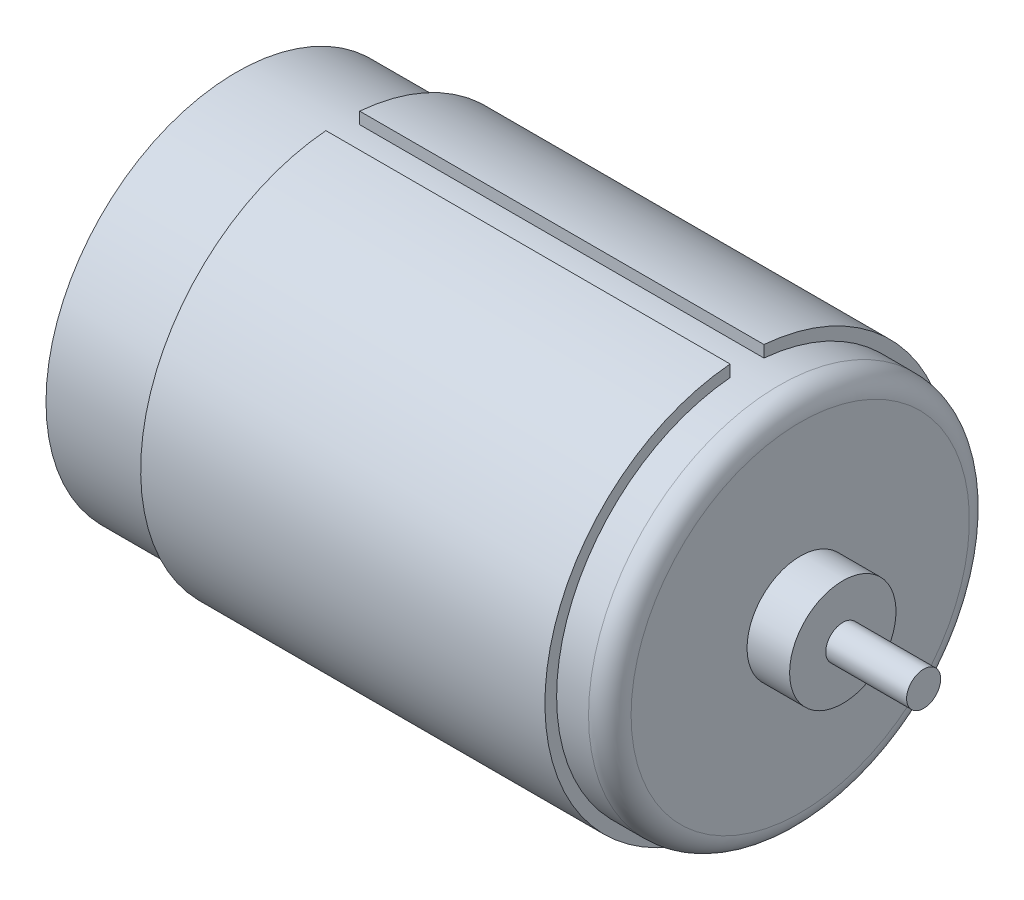
SolidWorks part; units mm, degrees
material "Plain Carbon Steel"
ref_plane "Front Plane" through (0, 0, 0) normal (0, 0, 1) x (1, 0, 0)
ref_plane "Top Plane" through (0, 0, 0) normal (0, 1, 0) x (1, 0, 0)
ref_plane "Right Plane" through (0, 0, 0) normal (1, 0, 0) x (0, 0, -1)
sketch "Sketch3" plane through (0, 0, 0) normal (0, 0, 1) x (1, 0, 0)
  line L0 (0, 0) -> (64.6, 0) construction
  line L1 (0, 0) -> (0, 17.9)
  line L2 (0, 17.9) -> (10, 17.9)
  line L3 (10, 17.9) -> (10, 19)
  line L4 (10, 19) -> (48, 19)
  line L5 (48, 19) -> (48, 17.9)
  line L6 (48, 17.9) -> (51, 17.9)
  line L7 (53, 15.9) -> (53, 5)
  line L8 (53, 5) -> (57, 5)
  line L9 (57, 5) -> (57, 1.6)
  line L10 (57, 1.6) -> (64.6, 1.6)
  line L11 (64.6, 1.6) -> (64.6, 0)
  line L12 (0, 0) -> (4.3018, 0)
  line L13 (49.6755, 14.9017) -> (49.6755, 0)
  line L14 (4.3018, 14.9017) -> (49.6755, 14.9017)
  line L15 (4.3018, 14.9017) -> (4.3018, 0)
  line L16 (49.6755, 0) -> (64.6, 0)
  arc A0 (51, 17.9) -> (53, 15.9) centre (51, 15.9) cw
  point P15 (53, 17.9)
  dimension "D10" = 2
  dimension "D1" = 7.6
  dimension "D2" = 3.2
  dimension "D3" = 57
  dimension "D4" = 35.8
  dimension "D5" = 38
  dimension "D6" = 4
  dimension "D7" = 10
  dimension "D8" = 5
  dimension "D9" = 10
revolve "Revolve1" add sketch "Sketch3" angle 360 about L0
sketch "Sketch4" plane through (10, 0, 0) normal (-1, 0, 0) x (0, 0, 1)
  line L0 (0, 17.9) -> (0, 0) construction
  line L1 (1.5875, 18.9336) -> (1.5875, 17.8295)
  line L2 (-1.5875, 18.9336) -> (-1.5875, 17.8295)
  arc A0 (-1.5875, 17.8295) -> (1.5875, 17.8295) centre (0, 0) cw
  circle A1 centre (0, 0) radius 17.9 construction
  arc A2 (-1.5875, 18.9336) -> (1.5875, 18.9336) centre (0, 0) cw
  circle A3 centre (0, 0) radius 19 construction
  dimension "D1" = 3.175
extrude "Cut-Extrude1" cut sketch "Sketch4" against normal up to next
